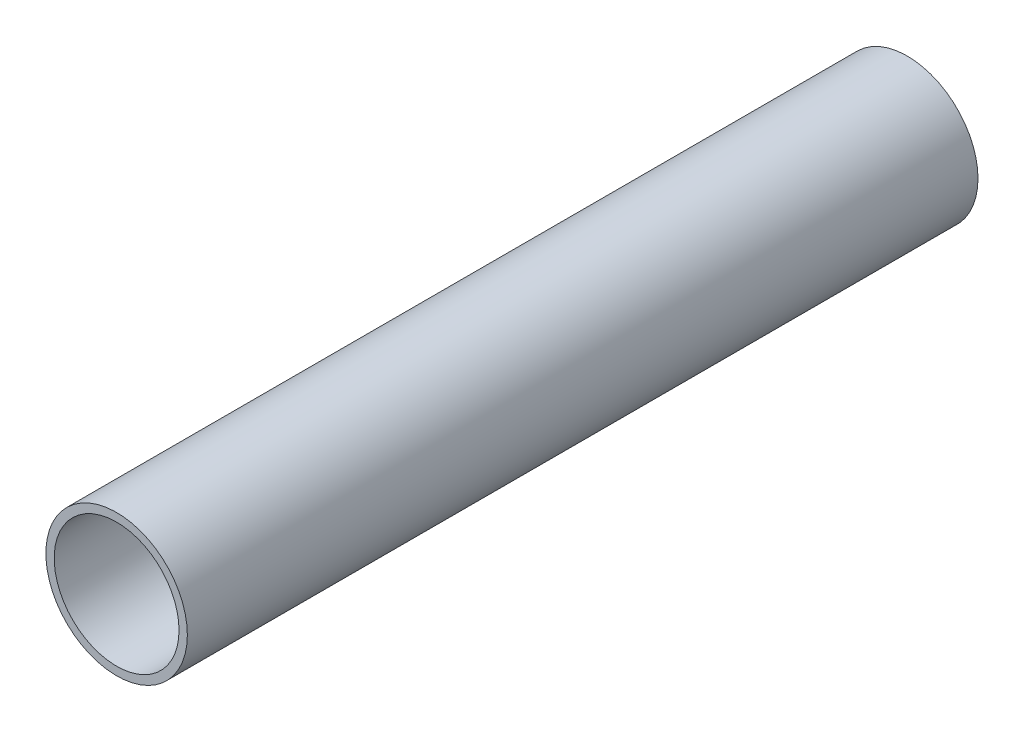
SolidWorks part; units mm, degrees
ref_plane "Front Plane" through (0, 0, 0) normal (0, 0, 1) x (1, 0, 0)
ref_plane "Top Plane" through (0, 0, 0) normal (0, 1, 0) x (1, 0, 0)
ref_plane "Right Plane" through (0, 0, 0) normal (1, 0, 0) x (0, 0, -1)
sketch "Sketch1" plane through (0, 0, 0) normal (0, 0, 1) x (1, 0, 0)
  circle A0 centre (0, 0) radius 15
  circle A1 centre (0, 0) radius 17
  dimension "D1" = 30
  dimension "D2" = 2
extrude "Boss-Extrude1" add sketch "Sketch1" along normal mid plane 190 contours A1 A0
